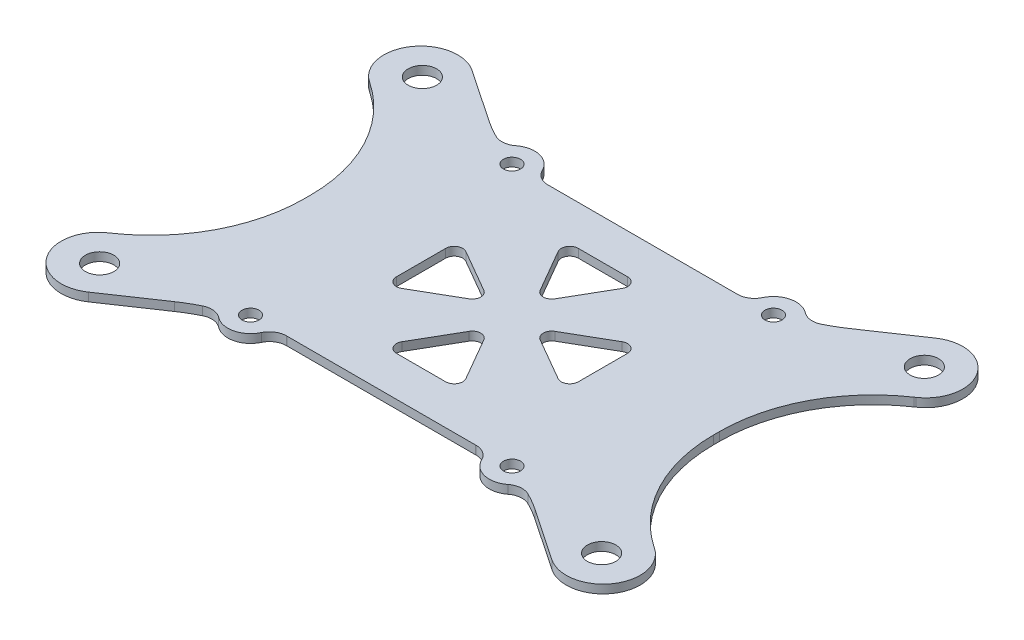
SolidWorks part; units mm, degrees
ref_plane "Front Plane" through (0, 0, 0) normal (0, 0, 1) x (1, 0, 0)
ref_plane "Top Plane" through (0, 0, 0) normal (0, 1, 0) x (1, 0, 0)
ref_plane "Right Plane" through (0, 0, 0) normal (1, 0, 0) x (0, 0, -1)
sketch "Sketch1" plane through (0, 0, 0) normal (0, 1, 0) x (1, 0, 0)
  line L1 (-36, -23) -> (36, -23)
  line L2 (-36, -23) -> (-36, 23)
  line L3 (-36, 23) -> (36, 23)
  line L4 (36, -23) -> (36, 23)
  line L5 (-36, -23) -> (36, 23) construction
  line L6 (-36, 23) -> (36, -23) construction
  point P0 (0, 0)
  dimension "D1" = 72
  dimension "D2" = 46
extrude "Boss-Extrude1" add sketch "Sketch1" along normal blind 1.5
sketch "Sketch2" plane through (0, 0, 0) normal (0, -1, 0) x (-1, 0, 0)
  line L0 (0, 0) -> (-36, -23) construction
  line L1 (-36, -23) -> (-93.2441, -59.5726) construction
  line L2 (0, 0) -> (44.427, 28.3839) construction
  line L3 (0, 0) -> (36, -23) construction
  line L4 (36, -23) -> (90.4744, -57.8031) construction
  line L5 (0, 0) -> (-36, 23) construction
  line L6 (-36, 23) -> (-93.2441, 59.5726) construction
  line L8 (48.0689, -23) -> (31.5438, -11.8216)
  line L9 (40.785, -33.7678) -> (24.2599, -22.5894)
  line L10 (31.5438, -11.8216) -> (24.2599, -22.5894)
  line L11 (48.0689, 23) -> (32.0813, 12.1852)
  line L12 (40.785, 33.7678) -> (24.7975, 22.953)
  line L13 (32.0813, 12.1852) -> (24.7975, 22.953)
  line L14 (49.9045, 31.8834) -> (152.7787, 97.6086) construction
  line L15 (-40.785, 33.7678) -> (-24.5168, 22.7631)
  line L16 (-48.0689, 23) -> (-31.8006, 11.9953)
  line L17 (-24.5168, 22.7631) -> (-31.8006, 11.9953)
  line L18 (-48.0689, -23) -> (-31.5915, -11.8538)
  line L19 (-40.785, -33.7678) -> (-24.3076, -22.6216)
  line L20 (-31.5915, -11.8538) -> (-24.3076, -22.6216)
  arc A0 (-48.0689, -23) -> (-40.785, -33.7678) centre (-44.427, -28.3839) ccw
  arc A1 (40.785, -33.7678) -> (48.0689, -23) centre (44.427, -28.3839) ccw
  arc A2 (48.0689, 23) -> (40.785, 33.7678) centre (44.427, 28.3839) ccw
  arc A3 (-40.785, 33.7678) -> (-48.0689, 23) centre (-44.427, 28.3839) ccw
  dimension "D1" = 10
  dimension "D2" = 10
  dimension "D3" = 10
  dimension "D4" = 10
extrude "Boss-Extrude2" add sketch "Sketch2" against normal blind 1.5
fillet "Fillet1" radius 27 4 edges at (36, 0.75, 14.836) (36, 0.75, -14.836) (-36, 0.75, 14.836) (-36, 0.75, -14.836)
fillet "Fillet2" radius 27 4 edges at (-24.867, 0.75, -23) (24.867, 0.75, -23) (24.867, 0.75, 23) (-24.867, 0.75, 23)
sketch "Sketch4" plane through (0, 1.5, 0) normal (0, 1, 0) x (1, 0, 0)
  circle A2 centre (-44.16, -28.3926) radius 2.5
  circle A3 centre (44.16, 28.3926) radius 2.5
  circle A4 centre (-44.16, 28.3926) radius 2.5
  circle A5 centre (44.16, -28.3926) radius 2.5
  point P7 (0, 0)
  point P14 (0, 0)
  dimension "D1" = 52.5
  dimension "D2" = 52.5
  dimension "D3" = 52.5
  dimension "D4" = 52.5
extrude "Cut-Extrude1" cut sketch "Sketch4" against normal through all
sketch "Sketch5" plane through (0, 1.5, 0) normal (0, 1, 0) x (1, 0, 0)
  line L1 (1.299, 6.25) -> (5.6292, 13.75)
  line L2 (4.3301, 16) -> (-4.3301, 16)
  line L3 (-5.6292, 13.75) -> (-1.299, 6.25)
  line L4 (-1.299, -6.25) -> (-5.6292, -13.75)
  line L5 (-4.3301, -16) -> (4.3301, -16)
  line L6 (5.6292, -13.75) -> (1.299, -6.25)
  line L7 (-6.25, 1.299) -> (-13.75, 5.6292)
  line L8 (-16, 4.3301) -> (-16, -4.3301)
  line L9 (-13.75, -5.6292) -> (-6.25, -1.299)
  line L10 (6.25, -1.299) -> (13.75, -5.6292)
  line L11 (16, -4.3301) -> (16, 4.3301)
  line L12 (13.75, 5.6292) -> (6.25, 1.299)
  circle A0 centre (0, 12) radius 4 construction
  circle A1 centre (0, -12) radius 4 construction
  circle A2 centre (-12, 0) radius 4 construction
  circle A3 centre (12, 0) radius 4 construction
  arc A4 (16, 4.3301) -> (13.75, 5.6292) centre (14.5, 4.3301) ccw
  arc A5 (13.75, -5.6292) -> (16, -4.3301) centre (14.5, -4.3301) ccw
  arc A6 (6.25, -1.299) -> (6.25, 1.299) centre (7, 0) cw
  arc A7 (5.6292, 13.75) -> (4.3301, 16) centre (4.3301, 14.5) ccw
  arc A8 (-4.3301, 16) -> (-5.6292, 13.75) centre (-4.3301, 14.5) ccw
  arc A9 (1.299, 6.25) -> (-1.299, 6.25) centre (0, 7) cw
  arc A10 (-1.299, -6.25) -> (1.299, -6.25) centre (0, -7) cw
  arc A11 (4.3301, -16) -> (5.6292, -13.75) centre (4.3301, -14.5) ccw
  arc A12 (-5.6292, -13.75) -> (-4.3301, -16) centre (-4.3301, -14.5) ccw
  arc A13 (-6.25, 1.299) -> (-6.25, -1.299) centre (-7, 0) cw
  arc A14 (-13.75, 5.6292) -> (-16, 4.3301) centre (-14.5, 4.3301) ccw
  arc A15 (-16, -4.3301) -> (-13.75, -5.6292) centre (-14.5, -4.3301) ccw
  point P27 (4, 0)
  point P34 (0, 4)
  point P37 (0, -4)
  point P44 (-4, 0)
  dimension "D9" = 1.5
  dimension "D1" = 4
  dimension "D2" = 16
  dimension "D3" = 4
  dimension "D4" = 16
  dimension "D5" = 4
  dimension "D6" = 16
  dimension "D7" = 4
  dimension "D8" = 16
extrude "Cut-Extrude2" cut sketch "Sketch5" against normal through all
sketch "Sketch6" plane through (0, 1.5, 0) normal (0, 1, 0) x (1, 0, 0)
  circle A0 centre (-23, -23) radius 4
  circle A1 centre (-23, 23) radius 4
  circle A2 centre (23, -23) radius 4
  circle A3 centre (23, 23) radius 4
extrude "Boss-Extrude3" add sketch "Sketch6" against normal blind 1.5
sketch "Sketch7" plane through (0, 1.5, 0) normal (0, 1, 0) x (1, 0, 0)
  circle A0 centre (-23, -23) radius 1.5
  circle A1 centre (-23, 23) radius 1.5
  circle A2 centre (23, -23) radius 1.5
  circle A3 centre (23, 23) radius 1.5
  dimension "D1" = 23
  dimension "D2" = 23
  dimension "D3" = 23
  dimension "D4" = 23
  dimension "D5" = 23
  dimension "D6" = 23
  dimension "D7" = 23
extrude "Cut-Extrude3" cut sketch "Sketch7" against normal through all
fillet "Fillet3" radius 3 8 edges at (-19.0014, 0.75, 23.1077) (-26.5238, 0.75, 24.8928) (19.0014, 0.75, 23.1077) (26.5238, 0.75, 24.8928) (-19.0014, 0.75, -23.1077) (-26.5238, 0.75, -24.8928) (19.0014, 0.75, -23.1077) (26.5238, 0.75, -24.8928)
